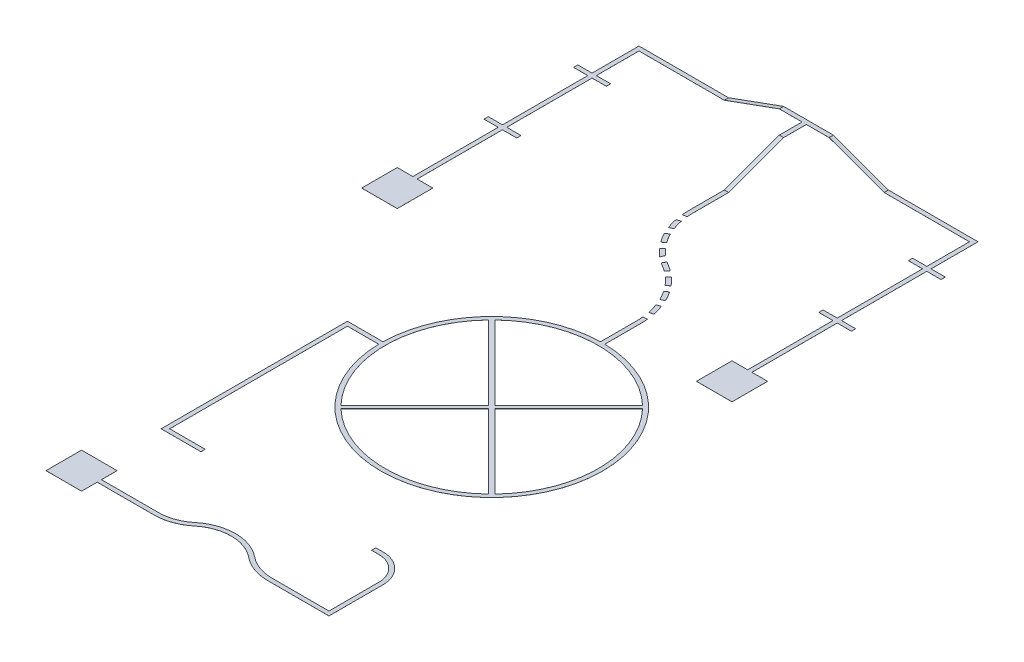
SolidWorks part; units mm, degrees
ref_plane "Front Plane" through (0, 0, 0) normal (0, 0, 1) x (1, 0, 0)
ref_plane "Top Plane" through (0, 0, 0) normal (0, 1, 0) x (1, 0, 0)
ref_plane "Right Plane" through (0, 0, 0) normal (1, 0, 0) x (0, 0, -1)
sketch "Sketch2" plane through (0, 0, 0) normal (0, 1, 0) x (1, 0, 0)
  line L0 (250, 140) -> (650, 140)
  line L1 (0, 0) -> (250, 0)
  line L2 (0, 0) -> (0, 250)
  line L3 (0, 250) -> (250, 250)
  line L4 (250, 0) -> (250, 110)
  line L5 (650, 140) -> (650, 110) construction
  line L6 (650, 110) -> (250, 110)
  line L7 (250, 140) -> (250, 250)
  line L8 (1450, 110) -> (1850, 110)
  line L9 (1450, 140) -> (1850, 140)
  line L10 (1850, 110) -> (1880, 110)
  line L11 (1880, 110) -> (1880, 490)
  line L12 (1880, 490) -> (1850, 490) construction
  line L13 (1850, 490) -> (1850, 140)
  line L17 (1680, 690) -> (1630, 690)
  line L18 (1680, 660) -> (1630, 660)
  line L19 (1630, 660) -> (1630, 690)
  arc A0 (650, 110) -> (859.5238, 185.0495) centre (650, 440) ccw
  arc A1 (859.5238, 185.0495) -> (1240.4762, 185.0495) centre (1050, -46.7237) cw
  arc A2 (1240.4762, 185.0495) -> (1450, 110) centre (1450, 440) ccw
  arc A3 (650, 140) -> (840.4762, 208.2268) centre (650, 440) ccw
  arc A4 (840.4762, 208.2268) -> (1259.5238, 208.2268) centre (1050, -46.7237) cw
  arc A5 (1259.5238, 208.2268) -> (1450, 140) centre (1450, 440) ccw
  arc A8 (1880, 490) -> (1680, 690) centre (1680, 490) ccw
  arc A9 (1850, 490) -> (1680, 660) centre (1680, 490) ccw
  point P30 (0, 0)
  dimension "D8" = 300
  dimension "D9" = 300
  dimension "D12" = 50
  dimension "D4" = 200
  dimension "D1" = 250
  dimension "D2" = 250
  dimension "D3" = 30
  dimension "D5" = 400
  dimension "D6" = 800
  dimension "D7" = 400
  dimension "D10" = 30
  dimension "D11" = 350
extrude "Boss-Extrude1" add sketch "Sketch2" along normal blind 0.2 contours L0 A3 A4 A5 L9 L13 A9 L18 L19 L17 A8 L11 L10 L8 A2 A1 A0 L6 L4 L1 L2 L3 L7
sketch "Sketch3" plane through (0, 0, 0) normal (0, 1, 0) x (1, 0, 0)
  line L0 (430, 660) -> (150, 660)
  line L1 (150, 660) -> (150, 1970)
  line L2 (150, 1970) -> (400, 1970)
  line L3 (430, 690) -> (180, 690)
  line L4 (180, 690) -> (180, 1940)
  line L5 (180, 1940) -> (400, 1940)
  line L6 (430, 660) -> (430, 690)
  line L7 (1630, 660) -> (1630, 690) construction
  line L8 (639.0251, 2474.6174) -> (1699.4732, 1414.1694)
  line L9 (660.2383, 2495.8306) -> (1720.6864, 1435.3826)
  line L10 (1169.2492, 1944.3934) -> (1190.4624, 1965.6066) construction
  line L11 (1720.6864, 2474.6174) -> (660.2383, 1414.1694)
  line L12 (1699.4732, 2495.8306) -> (639.0251, 1435.3826)
  line L13 (1164.8558, 2834.8558) -> (1164.8558, 2734.8558)
  line L14 (1194.8558, 2834.8558) -> (1194.8558, 2734.8558)
  line L15 (1164.8558, 2834.8558) -> (1194.8558, 2834.8558)
  arc A0 (639.0251, 2474.6174) -> (639.0251, 1435.3826) centre (1179.8558, 1955) ccw
  arc A1 (400, 1940) -> (1194.8558, 2734.8558) centre (1179.8558, 1955) ccw
  circle A2 centre (1179.8558, 1955) radius 780 construction
  circle A3 centre (1179.8558, 1955) radius 750 construction
  arc A4 (1699.4732, 2495.8306) -> (660.2383, 2495.8306) centre (1179.8558, 1955) ccw
  arc A5 (1720.6864, 1435.3826) -> (1720.6864, 2474.6174) centre (1179.8558, 1955) ccw
  arc A6 (660.2383, 1414.1694) -> (1699.4732, 1414.1694) centre (1179.8558, 1955) ccw
  arc A7 (1164.8558, 2734.8558) -> (400, 1970) centre (1179.8558, 1955) ccw
  point P21 (1179.8558, 1955)
  dimension "D4" = 1500
  dimension "D5" = 30
  dimension "D8" = 30
  dimension "D1" = 1200
  dimension "D2" = 30
  dimension "D3" = 250
  dimension "D6" = 1250
  dimension "D7" = 250
  dimension "D9" = 45
  dimension "D10" = 30
  dimension "D11" = 100
extrude "Boss-Extrude3" add sketch "Sketch3" along normal blind 0.2 separate body contours L5 A1 L2 L1 L0 L6 L3 L4 A6 L11 L8 L12 A0 L9 A4 A5 | L9 L12 L8 L11
sketch "Sketch5" plane through (0, 0, 0) normal (0, 1, 0) x (1, 0, 0)
  line L0 (1164.8558, 2834.8558) -> (1164.8558, 2984.8558)
  line L1 (676.122, 3844.2782) -> (706.122, 3844.2782) construction
  line L2 (1194.8558, 2984.8558) -> (1194.8558, 2834.8558)
  line L3 (1194.8558, 2834.8558) -> (1194.8558, 2734.8558) construction
  line L4 (1164.8558, 2834.8558) -> (1164.8558, 2734.8558) construction
  line L5 (676.122, 3844.2782) -> (676.122, 4094.2782)
  line L6 (676.122, 4094.2782) -> (706.122, 4094.2782)
  line L7 (706.122, 4094.2782) -> (706.122, 3844.2782)
  line L8 (1164.8558, 2834.8558) -> (1194.8558, 2834.8558)
  line L9 (1142.4574, 3032.7793) -> (1240.3796, 3042.605)
  line L10 (1135.2863, 3080.224) -> (1231.7382, 3099.7772)
  line L11 (1116.2887, 3147.9763) -> (1208.8455, 3181.4208)
  line L12 (1097.747, 3192.2327) -> (1186.5023, 3234.751)
  line L13 (1062.777, 3253.2933) -> (1144.3624, 3308.3308)
  line L14 (1164.8558, 2984.8558) -> (1194.8558, 2984.8558) construction
  line L15 (1033.9877, 3291.6808) -> (1109.6705, 3354.5888)
  line L16 (985.1635, 3342.3512) -> (1050.8359, 3415.6481)
  line L17 (947.8704, 3372.5447) -> (1005.8967, 3452.0322)
  line L18 (888.1492, 3409.7558) -> (933.9308, 3496.8727)
  line L19 (844.6112, 3429.9265) -> (881.4662, 3521.179)
  line L28 (727.2765, 3805.348) -> (630.4266, 3787.8723)
  line L29 (736.3697, 3759.1422) -> (641.7485, 3732.0843)
  line L30 (761.8823, 3694.4359) -> (672.2785, 3653.7362)
  line L31 (782.0322, 3651.8726) -> (696.9397, 3602.4301)
  line L32 (822.6382, 3595.4018) -> (745.7562, 3533.9651)
  line L33 (852.6136, 3559.0819) -> (782.2496, 3490.2762)
  line L34 (777.6102, 3451.4246) -> (800.7281, 3547.0847) [skipped]
  line L35 (730.4642, 3460.3508) -> (743.9159, 3557.8411) [skipped]
  arc A0 (1164.8558, 2984.8558) -> (920.4889, 3414.567) centre (664.8558, 2984.8558) ccw
  arc A1 (920.4889, 3414.567) -> (676.122, 3844.2782) centre (1176.122, 3844.2782) cw
  arc A2 (1194.8558, 2984.8558) -> (935.8268, 3440.3496) centre (664.8558, 2984.8558) ccw
  arc A3 (935.8268, 3440.3496) -> (706.122, 3844.2782) centre (1176.122, 3844.2782) cw
  arc A4 (920.4889, 3414.567) -> (676.122, 3844.2782) centre (1176.122, 3844.2782) cw construction
  arc A5 (1164.8558, 2984.8558) -> (920.4889, 3414.567) centre (664.8558, 2984.8558) ccw construction
  point P3 (841.4702, 3422.1496)
  point P26 (664.8558, 2984.8558)
  point P47 (664.8558, 2984.8558)
  dimension "D1" = 500
  dimension "D3" = 5.73
  dimension "D2" = 150
  dimension "D4" = 250
  dimension "D5" = 5.73
  dimension "D6" = 480
  dimension "D7" = 480
  dimension "D8" = 97.9222
  dimension "D9" = 6
extrude "Boss-Extrude4" add sketch "Sketch5" along normal blind 0.2 contours L2 A2 L9 A0 L0 L8 | L10 A2 L11 A0 | L12 A2 L13 A0 | L15 A2 L16 A0 | A2 A3 L18 A1 A0 L17 | L19 A3 L33 A1 | L32 A3 L31 A1 | L30 A3 L29 A1 | L28 A3 L7 L6 L5 A1
ref_plane "Plane1" through (0, -1315.699, -478.8753) normal (0, 0.9397, 0.342) x (1, 0, 0)
sketch "Sketch6" plane through (0, -1315.699, -478.8753) normal (0, 0.9397, 0.342) x (1, 0, 0)
  line L0 (676.122, 3847.4314) -> (676.122, 4259.4314)
  line L1 (676.122, 3847.4314) -> (706.122, 3847.4314)
  line L2 (706.122, 3847.4314) -> (706.122, 4259.4314)
  line L3 (676.122, 4259.4314) -> (706.122, 4259.4314)
  dimension "D1" = 412
extrude "Boss-Extrude5" add sketch "Sketch6" against normal blind 0.2 separate body
ref_plane "Plane2" through (0, 141.1123, 0) normal (0, 1, 0) x (1, 0, 0)
sketch "Sketch7" plane through (0, 141.1123, 0) normal (0, 1, 0) x (1, 0, 0)
  line L0 (676.122, 4481.4315) -> (676.122, 4641.4315)
  line L1 (676.122, 4641.4315) -> (516.122, 4641.4315)
  line L2 (516.122, 4641.4315) -> (516.122, 4671.4315)
  line L3 (516.122, 4671.4315) -> (866.122, 4671.4315)
  line L4 (866.122, 4671.4315) -> (866.122, 4641.4315)
  line L5 (866.122, 4641.4315) -> (706.122, 4641.4315)
  line L6 (706.122, 4641.4315) -> (706.122, 4481.4315)
  line L7 (676.122, 4481.4315) -> (706.122, 4481.4315)
  dimension "D1" = 30
  dimension "D2" = 160
  dimension "D3" = 160
extrude "Boss-Extrude6" add sketch "Sketch7" against normal blind 0.2
ref_plane "Plane3" through (15.0222, -41.2731, 0) normal (-0.342, 0.9397, 0) x (0, 0, 1)
sketch "Sketch8" plane through (15.0222, -41.2731, 0) normal (-0.342, 0.9397, 0) x (0, 0, 1)
  line L4 (-4671.4315, 121.2593) -> (-4641.4315, 121.2593)
  line L5 (-4671.4315, 533.2593) -> (-4671.4315, 121.2593)
  line L6 (-4641.4315, 121.2593) -> (-4641.4315, 533.2593)
  line L7 (-4641.4315, 533.2593) -> (-4671.4315, 533.2593)
  dimension "D1" = 412
extrude "Boss-Extrude7" add sketch "Sketch8" against normal blind 0.2
ref_plane "Plane4" through (146.6696, 402.9715, 0) normal (0.342, 0.9397, 0) x (0, 0, -1)
sketch "Sketch9" plane through (146.6696, 402.9715, 0) normal (0.342, 0.9397, 0) x (0, 0, -1)
  line L0 (4641.4315, -765.6252) -> (4671.4315, -765.6252)
  line L1 (4671.4315, -765.6252) -> (4671.4315, -1177.6252)
  line L2 (4671.4315, -1177.6252) -> (4641.4315, -1177.6252)
  line L3 (4641.4315, -1177.6252) -> (4641.4315, -765.6252)
  point P4 (0, 0)
  point P7 (0, 0)
  dimension "D1" = 412
extrude "Boss-Extrude8" add sketch "Sketch9" against normal blind 0.2
sketch "Sketch10" plane through (0, 0, 0) normal (0, 1, 0) x (1, 0, 0)
  line L0 (128.9686, 4641.4315) -> (-471.0314, 4641.4315)
  line L1 (-471.0314, 4641.4315) -> (-471.0314, 4341.4315)
  line L2 (-471.0314, 4341.4315) -> (-371.0314, 4341.4315)
  line L3 (-371.0314, 4341.4315) -> (-371.0314, 4311.4315)
  line L4 (-371.0314, 4311.4315) -> (-471.0314, 4311.4315)
  line L5 (-471.0314, 4311.4315) -> (-471.0314, 3711.4315)
  line L6 (-471.0314, 3711.4315) -> (-371.0314, 3711.4315)
  line L7 (-371.0314, 3711.4315) -> (-371.0314, 3681.4315)
  line L8 (-371.0314, 3681.4315) -> (-471.0314, 3681.4315)
  line L9 (-471.0314, 3681.4315) -> (-471.0314, 3081.4315)
  line L10 (-471.0314, 3081.4315) -> (-361.0314, 3081.4315)
  line L11 (-361.0314, 3081.4315) -> (-361.0314, 2831.4315)
  line L12 (-361.0314, 2831.4315) -> (-611.0314, 2831.4315)
  line L13 (-611.0314, 2831.4315) -> (-611.0314, 3081.4315)
  line L14 (-611.0314, 3081.4315) -> (-501.0314, 3081.4315)
  line L15 (-501.0314, 3081.4315) -> (-501.0314, 3681.4315)
  line L16 (-501.0314, 3681.4315) -> (-601.0314, 3681.4315)
  line L17 (-601.0314, 3681.4315) -> (-601.0314, 3711.4315)
  line L18 (-601.0314, 3711.4315) -> (-501.0314, 3711.4315)
  line L19 (-501.0314, 3711.4315) -> (-501.0314, 4311.4315)
  line L20 (-501.0314, 4311.4315) -> (-601.0314, 4311.4315)
  line L21 (-601.0314, 4311.4315) -> (-601.0314, 4341.4315)
  line L22 (-601.0314, 4341.4315) -> (-501.0314, 4341.4315)
  line L23 (-501.0314, 4341.4315) -> (-501.0314, 4671.4315)
  line L24 (-501.0314, 4671.4315) -> (128.9686, 4671.4315)
  line L25 (128.9686, 4641.4315) -> (128.9686, 4671.4315)
  line L26 (691.122, 4671.4315) -> (691.122, 4481.4315) construction
  line L27 (866.122, 4671.4315) -> (516.122, 4671.4315) construction
  line L28 (706.122, 4481.4315) -> (676.122, 4481.4315) construction
  line L29 (1253.2753, 4641.4315) -> (1253.2753, 4671.4315)
  line L30 (1883.2753, 4671.4315) -> (1253.2753, 4671.4315)
  line L31 (1883.2753, 4341.4315) -> (1883.2753, 4671.4315)
  line L32 (1983.2753, 4341.4315) -> (1883.2753, 4341.4315)
  line L33 (1983.2753, 4311.4315) -> (1983.2753, 4341.4315)
  line L34 (1883.2753, 4311.4315) -> (1983.2753, 4311.4315)
  line L35 (1883.2753, 3711.4315) -> (1883.2753, 4311.4315)
  line L36 (1983.2753, 3711.4315) -> (1883.2753, 3711.4315)
  line L37 (1983.2753, 3681.4315) -> (1983.2753, 3711.4315)
  line L38 (1883.2753, 3681.4315) -> (1983.2753, 3681.4315)
  line L39 (1883.2753, 3081.4315) -> (1883.2753, 3681.4315)
  line L40 (1993.2753, 3081.4315) -> (1883.2753, 3081.4315)
  line L41 (1993.2753, 2831.4315) -> (1993.2753, 3081.4315)
  line L42 (1743.2753, 2831.4315) -> (1993.2753, 2831.4315)
  line L43 (1743.2753, 3081.4315) -> (1743.2753, 2831.4315)
  line L44 (1853.2753, 3081.4315) -> (1743.2753, 3081.4315)
  line L45 (1853.2753, 3681.4315) -> (1853.2753, 3081.4315)
  line L46 (1753.2753, 3681.4315) -> (1853.2753, 3681.4315)
  line L47 (1753.2753, 3711.4315) -> (1753.2753, 3681.4315)
  line L48 (1853.2753, 3711.4315) -> (1753.2753, 3711.4315)
  line L49 (1853.2753, 4311.4315) -> (1853.2753, 3711.4315)
  line L50 (1753.2753, 4311.4315) -> (1853.2753, 4311.4315)
  line L51 (1753.2753, 4341.4315) -> (1753.2753, 4311.4315)
  line L52 (1853.2753, 4341.4315) -> (1753.2753, 4341.4315)
  line L53 (1853.2753, 4641.4315) -> (1853.2753, 4341.4315)
  line L54 (1253.2753, 4641.4315) -> (1853.2753, 4641.4315)
  point P60 (-171.0656, 4789.4451)
  point P61 (0, 0)
  dimension "D1" = 30
  dimension "D2" = 250
  dimension "D3" = 250
  dimension "D4" = 600
  dimension "D5" = 600
  dimension "D6" = 30
  dimension "D7" = 300
  dimension "D8" = 100
  dimension "D9" = 600
extrude "Boss-Extrude9" add sketch "Sketch10" along normal blind 0.2 separate body
